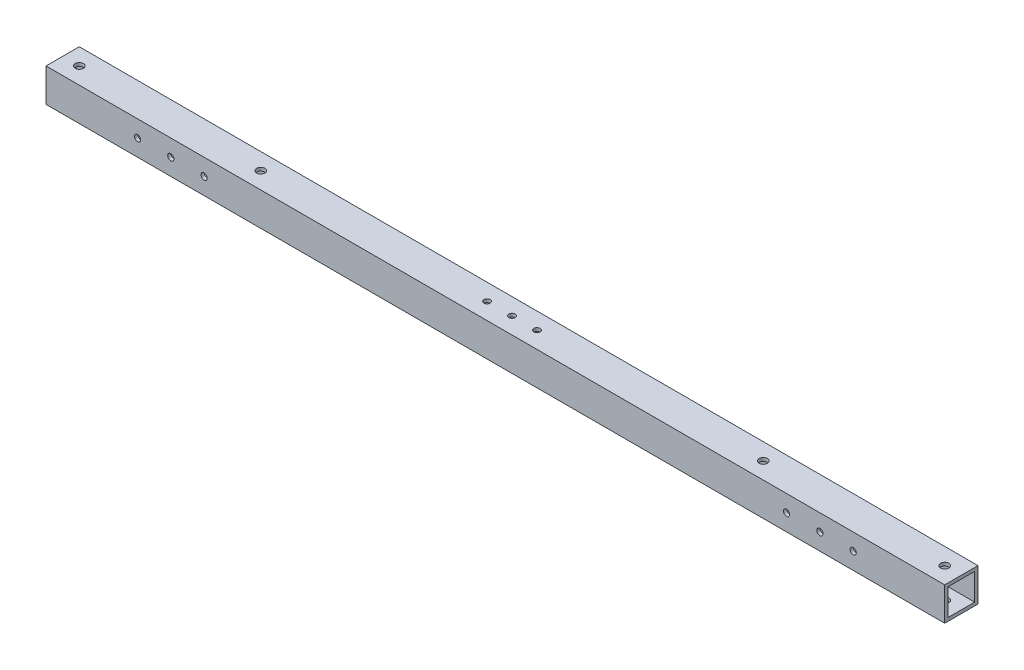
SolidWorks part; units mm, degrees
ref_plane "Front Plane" through (0, 0, 0) normal (0, 0, 1) x (1, 0, 0)
ref_plane "Top Plane" through (0, 0, 0) normal (0, 1, 0) x (1, 0, 0)
ref_plane "Right Plane" through (0, 0, 0) normal (1, 0, 0) x (0, 0, -1)
sketch "Sketch1" plane through (0, 0, 0) normal (1, 0, 0) x (0, 0, -1)
  line L0 (10.16, 10.16) -> (-10.16, 10.16)
  line L1 (12.7, -12.7) -> (-12.7, -12.7)
  line L2 (12.7, -12.7) -> (12.7, 12.7)
  line L3 (12.7, 12.7) -> (-12.7, 12.7)
  line L4 (-12.7, -12.7) -> (-12.7, 12.7)
  line L5 (12.7, -12.7) -> (-12.7, 12.7) construction
  line L6 (12.7, 12.7) -> (-12.7, -12.7) construction
  line L7 (-10.16, -10.16) -> (-10.16, 10.16)
  line L8 (10.16, -10.16) -> (-10.16, -10.16)
  line L9 (10.16, -10.16) -> (10.16, 10.16)
  point P0 (0, 0)
  dimension "D1" = 25.4
  dimension "D2" = 25.4
  dimension "D3" = 2.54
extrude "Boss-Extrude1" add sketch "Sketch1" along normal blind 685.8
sketch "Sketch2" plane through (0, 12.7, 0) normal (0, 1, 0) x (1, 0, 0)
  line L0 (0, 0) -> (685.8, 0) construction
  line L1 (685.8, 12.7) -> (685.8, -12.7) construction
  line L2 (342.9, 12.7) -> (342.9, -12.7) construction
  line L3 (685.8, 12.7) -> (0, 12.7) construction
  line L4 (685.8, -12.7) -> (0, -12.7) construction
  circle A0 centre (673.1, 0) radius 3.175
  circle A1 centre (534.67, 0) radius 3.175
  circle A2 centre (151.13, 0) radius 3.175
  circle A3 centre (12.7, 0) radius 3.175
  dimension "D1" = 6.35
  dimension "D2" = 12.7
  dimension "D3" = 2
extrude "Cut-Extrude1" cut sketch "Sketch2" against normal through all
sketch "Sketch3" plane through (0, 12.7, 0) normal (0, 1, 0) x (1, 0, 0)
  line L0 (685.8, 0) -> (0, 0) construction
  line L1 (685.8, 12.7) -> (685.8, -12.7) construction
  line L2 (342.9, -12.7) -> (342.9, 12.7) construction
  line L3 (685.8, -12.7) -> (0, -12.7) construction
  line L4 (685.8, 12.7) -> (0, 12.7) construction
  circle A0 centre (342.9, 0) radius 2.3813
  circle A1 centre (361.95, 0) radius 2.3813
  circle A2 centre (323.85, 0) radius 2.3813
  dimension "D1" = 4.7625
  dimension "D2" = 2
extrude "Cut-Extrude2" cut sketch "Sketch3" against normal through all
sketch "Sketch4" plane through (0, 0, 12.7) normal (0, 0, 1) x (1, 0, 0)
  line L0 (685.8, 0) -> (0, 0) construction
  line L1 (685.8, 12.7) -> (685.8, -12.7) construction
  line L2 (342.9, 12.7) -> (342.9, -12.7) construction
  line L3 (685.8, 12.7) -> (0, 12.7) construction
  line L4 (685.8, -12.7) -> (0, -12.7) construction
  circle A0 centre (615.95, 0) radius 2.3812
  circle A1 centre (590.55, 0) radius 2.3812
  circle A2 centre (565.15, 0) radius 2.3812
  circle A3 centre (120.65, 0) radius 2.3812
  circle A4 centre (95.25, 0) radius 2.3812
  circle A5 centre (69.85, 0) radius 2.3812
  dimension "D1" = 4.7625
  dimension "D2" = 69.85
  dimension "D3" = 3
extrude "Cut-Extrude3" cut sketch "Sketch4" against normal through all
